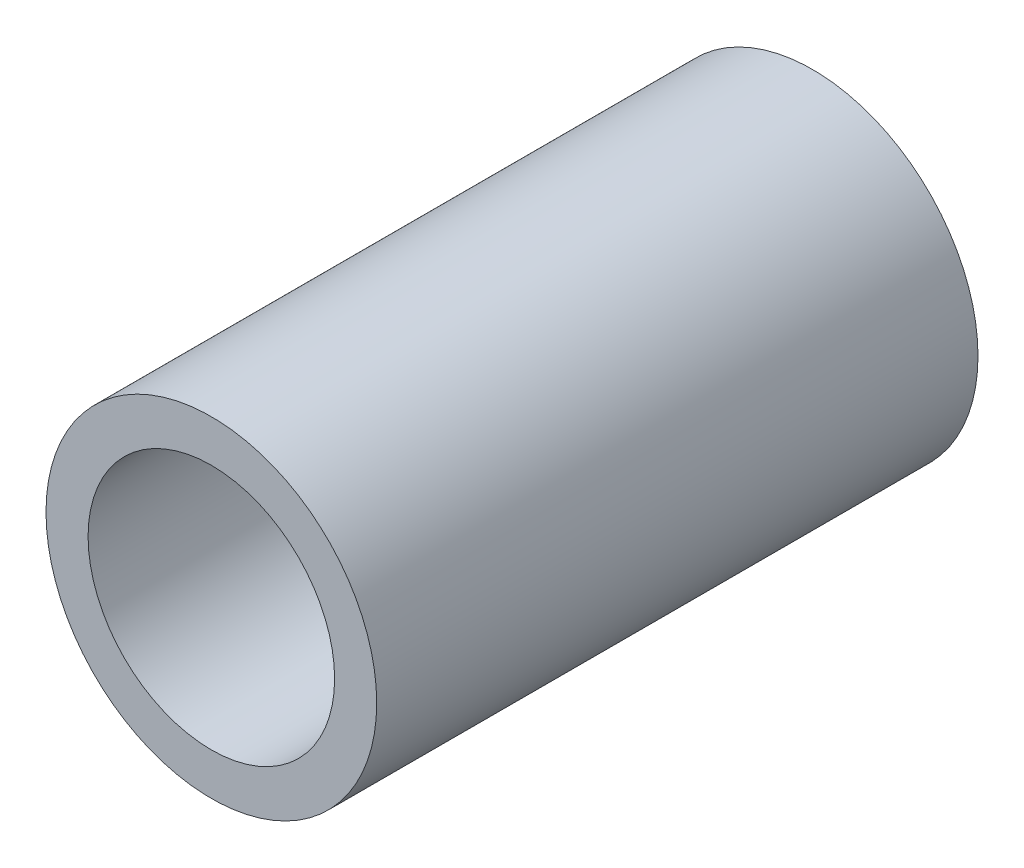
SolidWorks part; units mm, degrees
ref_plane "前视基准面" through (0, 0, 0) normal (0, 0, 1) x (1, 0, 0)
ref_plane "上视基准面" through (0, 0, 0) normal (0, 1, 0) x (1, 0, 0)
ref_plane "右视基准面" through (0, 0, 0) normal (1, 0, 0) x (0, 0, -1)
sketch "草图1" plane through (0, 0, 0) normal (0, 0, 1) x (1, 0, 0)
  circle A0 centre (0, 0) radius 4.125
  circle A1 centre (0, 0) radius 3.075
  dimension "D1" = 8.25
  dimension "D2" = 6.15
extrude "凸台-拉伸1" add sketch "草图1" along normal blind 15
